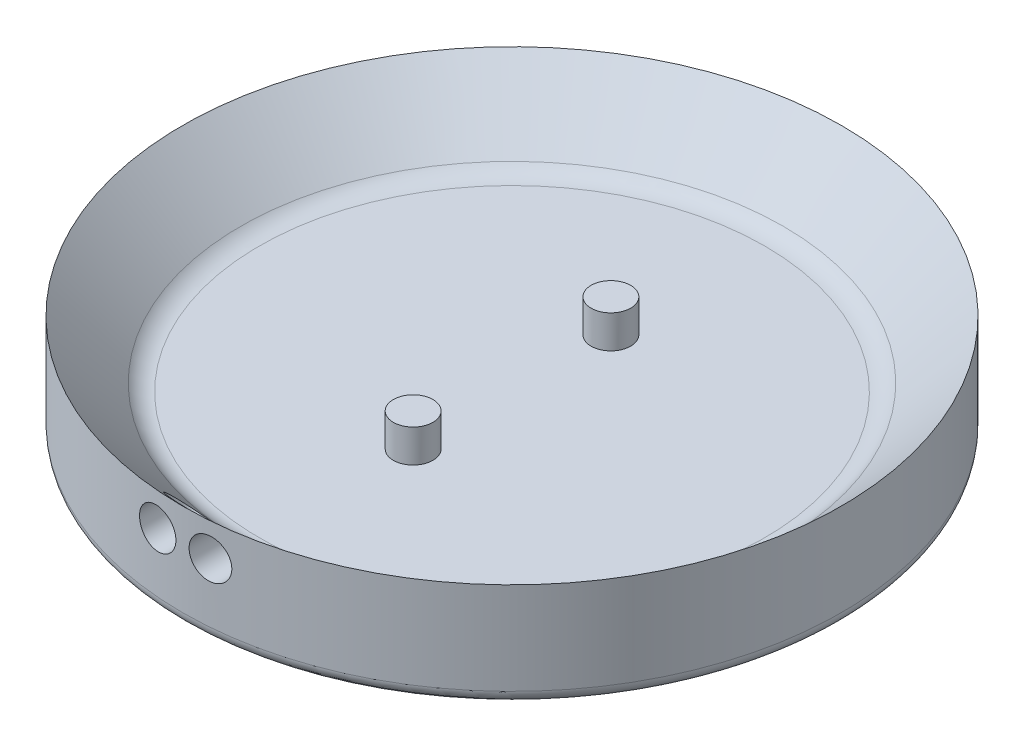
SolidWorks part; units mm, degrees
ref_plane "Front Plane" through (0, 0, 0) normal (0, 0, 1) x (1, 0, 0)
ref_plane "Top Plane" through (0, 0, 0) normal (0, 1, 0) x (1, 0, 0)
ref_plane "Right Plane" through (0, 0, 0) normal (1, 0, 0) x (0, 0, -1)
sketch "Sketch3" plane through (0, 0, 0) normal (0, 0, 1) x (1, 0, 0)
  line L4 (-23, 0) -> (0, 0)
  line L9 (-19.1716, 3) -> (0, 3)
  line L10 (0, 0) -> (0, 3)
  line L12 (-20, 3) -> (-20, 8) construction
  line L13 (-20, 8) -> (-25, 8) construction
  line L15 (-25, 8) -> (-20.5858, 3.5858)
  line L16 (-23, 0) -> (-24, 0)
  line L17 (-25, 1) -> (-25, 8)
  arc A4 (-25, 1) -> (-24, 0) centre (-24, 1) ccw
  arc A5 (-20.5858, 3.5858) -> (-19.1716, 3) centre (-19.1716, 5) ccw
  dimension "D1" = 5
  dimension "D6" = 1
  dimension "D7" = 2
  dimension "D2" = 23
  dimension "D3" = 20
  dimension "D4" = 3
  dimension "D5" = 5
revolve "Revolve3" add sketch "Sketch3" angle 360 about L10
ref_plane "Plane1" through (0, 0, 25) normal (0, 0, 1) x (1, 0, 0)
sketch "Sketch5" plane through (0, 0, 25) normal (0, 0, 1) x (1, 0, 0)
  line L0 (0, 8) -> (0, 3) construction
  line L2 (25, 8) -> (-25, 8) construction
  line L3 (-2, 5.5) -> (2, 5.5) construction
  circle A0 centre (-2, 5.5) radius 1.5
  circle A1 centre (2, 5.5) radius 1.5
  point P8 (0, 5.5)
  point P9 (0, 5.5)
  dimension "D3" = 3
  dimension "D4" = 3
  dimension "D1" = 5
  dimension "D2" = 4
extrude "Cut-Extrude1" cut sketch "Sketch5" against normal up to next
sketch "Sketch6" plane through (0, 3, 0) normal (0, 1, 0) x (1, 0, 0)
  line L0 (0, -7.5) -> (0, 7.5) construction
  circle A0 centre (0, 7.5) radius 1.5
  circle A1 centre (0, -7.5) radius 1.5
  point P2 (0, 0)
  dimension "D2" = 3
  dimension "D3" = 3
  dimension "D1" = 15
extrude "Boss-Extrude1" add sketch "Sketch6" along normal blind 2.5
